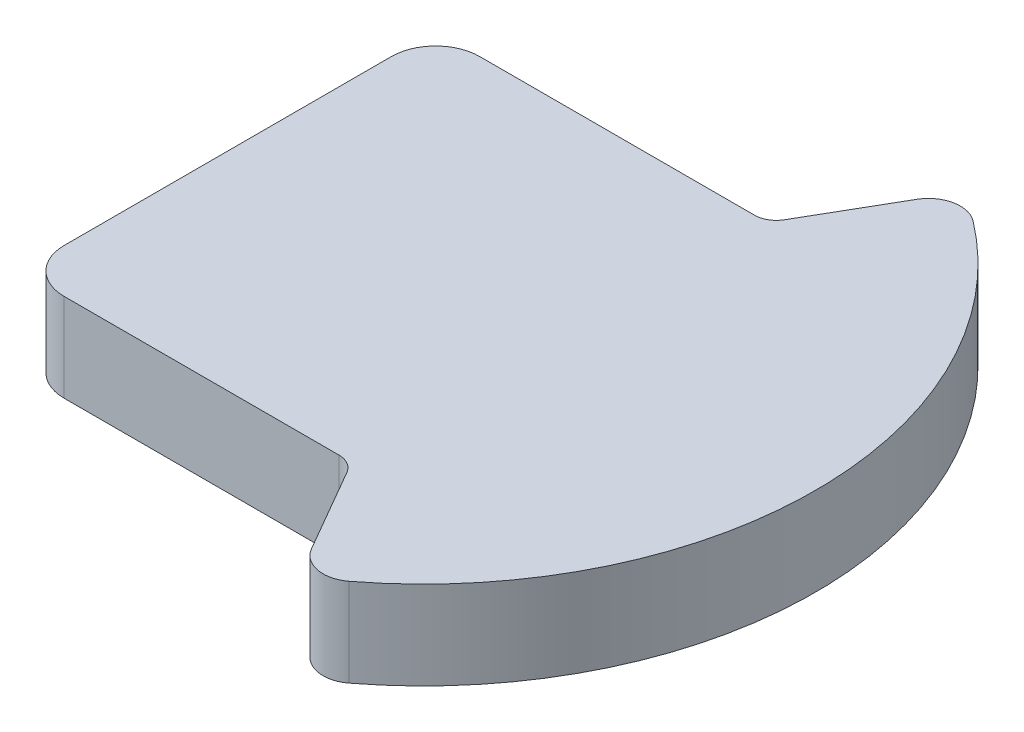
SolidWorks part; units mm, degrees
ref_plane "Front Plane" through (0, 0, 0) normal (0, 0, 1) x (1, 0, 0)
ref_plane "Top Plane" through (0, 0, 0) normal (0, 1, 0) x (1, 0, 0)
ref_plane "Right Plane" through (0, 0, 0) normal (1, 0, 0) x (0, 0, -1)
sketch "Sketch9" plane through (0, 0, 0) normal (0, 1, 0) x (1, 0, 0)
  line L0 (20.4957, 31.493) -> (27.4724, 43.5771)
  line L1 (-21.7956, 29.9055) -> (17.7461, 29.9055)
  line L2 (-28.1456, 23.5555) -> (-28.1456, -23.5555)
  line L3 (-21.7956, -29.9055) -> (17.7461, -29.9055)
  line L4 (37.575, 0) -> (51.514, 0)
  line L6 (20.4957, -31.493) -> (27.4724, -43.5771)
  arc A0 (34.2012, 44.929) -> (27.4724, 43.5771) centre (31.4319, 41.2911) ccw
  arc A1 (34.2012, -44.929) -> (34.2012, 44.929) centre (0, 0) ccw
  arc A2 (34.2012, -44.929) -> (27.4724, -43.5771) centre (31.4319, -41.2911) cw
  arc A3 (-21.7956, 29.9055) -> (-28.1456, 23.5555) centre (-21.7956, 23.5555) ccw
  arc A4 (-21.7956, -29.9055) -> (-28.1456, -23.5555) centre (-21.7956, -23.5555) cw
  arc A5 (20.4957, 31.493) -> (17.7461, 29.9055) centre (17.7461, 33.0805) cw
  arc A6 (20.4957, -31.493) -> (17.7461, -29.9055) centre (17.7461, -33.0805) ccw
  point P0 (0, 0)
  dimension "D1" = 4.572
  dimension "D2" = 6.35
  dimension "D3" = 3.175
sketch "Sketch10" plane through (0, 0, 0) normal (0, 0, 1) x (1, 0, 0)
  line L0 (51.514, 0) -> (51.514, -1.4003)
  line L1 (49.99, -2.9243) -> (48.2459, -2.9243)
  line L2 (46.7219, -4.4483) -> (46.7219, -4.8884)
  line L3 (45.1979, -6.4124) -> (39.099, -6.4124)
  line L4 (37.575, 0) -> (37.575, -4.8884)
  line L5 (0, 0) -> (0, 37.6483) construction
  line L6 (37.575, 0) -> (51.514, 0.5299)
  line L7 (51.514, 0) -> (51.514, 0.5299)
  arc A0 (51.514, -1.4003) -> (49.99, -2.9243) centre (49.99, -1.4003) cw
  arc A1 (45.1979, -6.4124) -> (46.7219, -4.8884) centre (45.1979, -4.8884) ccw
  arc A2 (37.575, -4.8884) -> (39.099, -6.4124) centre (39.099, -4.8884) ccw
  arc A3 (48.2459, -2.9243) -> (46.7219, -4.4483) centre (48.2459, -4.4483) ccw
  dimension "D1" = 1.524
extrude "Extrude4" add sketch "Sketch9" against normal blind 12.7
